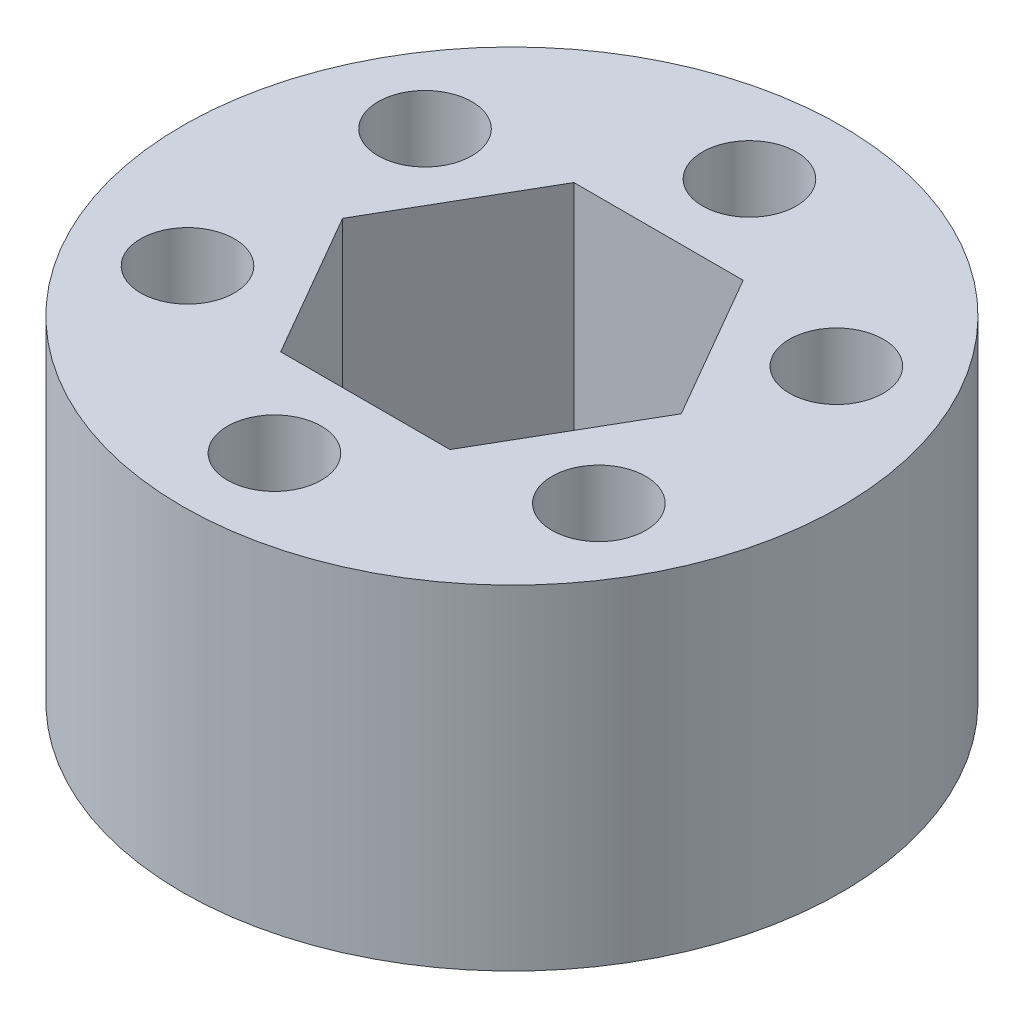
SolidWorks part; units mm, degrees
ref_plane "Front Plane" through (0, 0, 0) normal (0, 0, 1) x (1, 0, 0)
ref_plane "Top Plane" through (0, 0, 0) normal (0, 1, 0) x (1, 0, 0)
ref_plane "Right Plane" through (0, 0, 0) normal (1, 0, 0) x (0, 0, -1)
sketch "Sketch1" plane through (0, 0, 0) normal (0, 1, 0) x (1, 0, 0)
  line L0 (0, 14.2748) -> (0, -14.2748) construction
  line L1 (-12.3623, 7.1374) -> (12.3623, -7.1374) construction
  line L2 (-12.3623, -7.1374) -> (12.3623, 7.1374) construction
  line L4 (7.3323, 0) -> (3.6662, 6.35)
  line L5 (3.6662, 6.35) -> (-3.6662, 6.35)
  line L6 (-3.6662, 6.35) -> (-7.3323, 0)
  line L7 (-7.3323, 0) -> (-3.6662, -6.35)
  line L8 (-3.6662, -6.35) -> (3.6662, -6.35)
  line L9 (3.6662, -6.35) -> (7.3323, 0)
  circle A0 centre (0, 0) radius 14.2748
  circle A1 centre (0, 0) radius 10.287 construction
  circle A2 centre (0, 10.287) radius 2.032
  circle A3 centre (8.9088, 5.1435) radius 2.032
  circle A4 centre (8.9088, -5.1435) radius 2.032
  circle A5 centre (0, -10.287) radius 2.032
  circle A6 centre (-8.9088, -5.1435) radius 2.032
  circle A7 centre (-8.9088, 5.1435) radius 2.032
  circle A8 centre (0, 0) radius 6.35 construction
  point P12 (-8.9088, 5.1435)
  point P13 (-8.9088, -5.1435)
  point P14 (0, -10.287)
  point P15 (8.9088, -5.1435)
  point P16 (8.9088, 5.1435)
  dimension "D1" = 28.5496
  dimension "D4" = 4.064
  dimension "D2" = 60
  dimension "D3" = 60
  dimension "D5" = 12.7
extrude "Boss-Extrude1" add sketch "Sketch1" along normal blind 14.478
